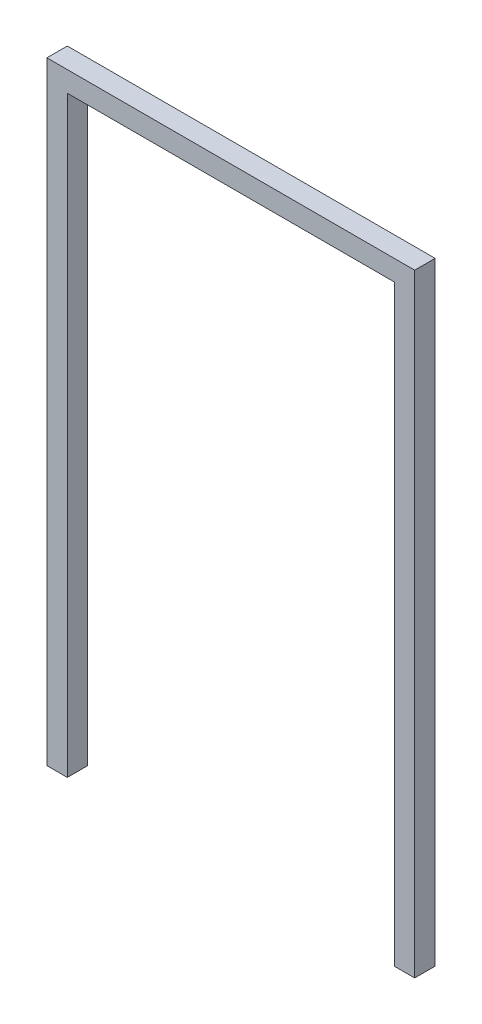
SolidWorks part; units mm, degrees
ref_plane "Front Plane" through (0, 0, 0) normal (0, 0, 1) x (1, 0, 0)
ref_plane "Top Plane" through (0, 0, 0) normal (0, 1, 0) x (1, 0, 0)
ref_plane "Right Plane" through (0, 0, 0) normal (1, 0, 0) x (0, 0, -1)
sketch "Sketch2" plane through (0, 0, 0) normal (0, 0, 1) x (1, 0, 0)
  line L0 (-160, -120) -> (160, -120) construction
  line L1 (-180, 340) -> (180, 340)
  line L2 (-180, 340) -> (-180, -260)
  line L3 (-180, -260) -> (-160, -260)
  line L4 (180, 340) -> (180, -260)
  line L7 (160, -260) -> (180, -260)
  line L8 (0, 320) -> (0, 0) construction
  line L9 (-160, 320) -> (160, 320)
  line L10 (-160, 320) -> (-160, -260)
  line L12 (160, 320) -> (160, -260)
  line L14 (-160, 0) -> (160, 0) construction
  dimension "D1" = 320
  dimension "D2" = 320
  dimension "D3" = 20
  dimension "D4" = 20
  dimension "D5" = 20
  dimension "D6" = 120
  dimension "D7" = 600
extrude "Boss-Extrude1" add sketch "Sketch2" against normal mid plane 20
